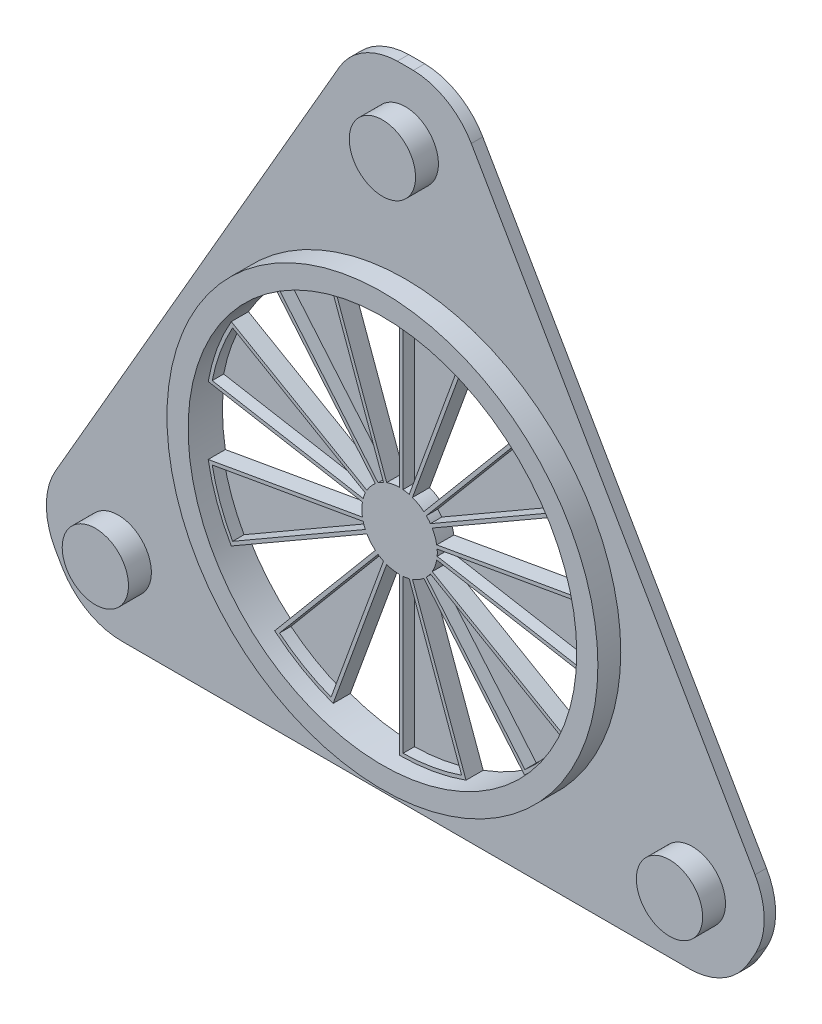
SolidWorks part; units mm, degrees
ref_plane "Спереди" through (0, 0, 0) normal (0, 0, 1) x (1, 0, 0)
ref_plane "Сверху" through (0, 0, 0) normal (0, 1, 0) x (1, 0, 0)
ref_plane "Справа" through (0, 0, 0) normal (1, 0, 0) x (0, 0, -1)
sketch "Sketch1" plane through (0, 0, 0) normal (0, 0, 1) x (1, 0, 0)
  line L0 (3.9, 6.755) -> (7.8, 0) construction
  line L2 (5.85, 10.1325) -> (11.7, 0) construction
  line L4 (7.8, 13.51) -> (15.6, 0) construction
  circle A61 centre (0, 0) radius 20
  circle A131 centre (0, 0) radius 1.25
  circle A484 centre (3.9, 0) radius 1.25
  circle A485 centre (7.8, 0) radius 1.25
  circle A486 centre (11.7, 0) radius 1.25
  circle A487 centre (15.6, 0) radius 1.25
  circle A488 centre (1.95, -3.3775) radius 1.25
  circle A489 centre (3.9, -6.755) radius 1.25
  circle A490 centre (5.85, -10.1325) radius 1.25
  circle A491 centre (7.8, -13.51) radius 1.25
  circle A492 centre (-1.95, -3.3775) radius 1.25
  circle A493 centre (-3.9, -6.755) radius 1.25
  circle A494 centre (-5.85, -10.1325) radius 1.25
  circle A495 centre (-7.8, -13.51) radius 1.25
  circle A496 centre (-3.9, 0) radius 1.25
  circle A497 centre (-7.8, 0) radius 1.25
  circle A498 centre (-11.7, 0) radius 1.25
  circle A499 centre (-15.6, 0) radius 1.25
  circle A500 centre (-1.95, 3.3775) radius 1.25
  circle A501 centre (-3.9, 6.755) radius 1.25
  circle A502 centre (-5.85, 10.1325) radius 1.25
  circle A503 centre (-7.8, 13.51) radius 1.25
  circle A504 centre (1.95, 3.3775) radius 1.25
  circle A505 centre (3.9, 6.755) radius 1.25
  circle A506 centre (5.85, 10.1325) radius 1.25
  circle A507 centre (7.8, 13.51) radius 1.25
  circle A508 centre (5.85, 3.3775) radius 1.25
  circle A509 centre (7.8, 6.755) radius 1.25
  circle A510 centre (9.75, 3.3775) radius 1.25
  circle A511 centre (11.7, 6.755) radius 1.25
  circle A512 centre (9.7491, 10.1341) radius 1.25
  circle A513 centre (13.6509, 3.3759) radius 1.25
  circle A514 centre (5.85, -3.3791) radius 1.25
  circle A515 centre (9.75, -3.3791) radius 1.25
  circle A516 centre (7.8, -6.7566) radius 1.25
  circle A517 centre (11.7, -6.7566) radius 1.25
  circle A518 centre (9.7491, -10.1356) radius 1.25
  circle A519 centre (13.6509, -3.3775) radius 1.25
  circle A520 centre (-0.0013, -6.7573) radius 1.25
  circle A521 centre (1.9487, -10.1348) radius 1.25
  circle A522 centre (-1.9513, -10.1348) radius 1.25
  circle A523 centre (-0.0013, -13.5123) radius 1.25
  circle A524 centre (-3.9032, -13.5123) radius 1.25
  circle A525 centre (3.9005, -13.5123) radius 1.25
  circle A526 centre (-5.8527, -3.3791) radius 1.25
  circle A527 centre (-7.8027, -6.7566) radius 1.25
  circle A528 centre (-9.7527, -3.3791) radius 1.25
  circle A529 centre (-11.7027, -6.7566) radius 1.25
  circle A530 centre (-13.6536, -3.3775) radius 1.25
  circle A531 centre (-9.7518, -10.1356) radius 1.25
  circle A532 centre (-5.8527, 3.3775) radius 1.25
  circle A533 centre (-9.7527, 3.3775) radius 1.25
  circle A534 centre (-7.8027, 6.755) radius 1.25
  circle A535 centre (-11.7027, 6.755) radius 1.25
  circle A536 centre (-9.7518, 10.1341) radius 1.25
  circle A537 centre (-13.6536, 3.3759) radius 1.25
  circle A538 centre (-0.0014, 6.7558) radius 1.25
  circle A539 centre (-1.9514, 10.1333) radius 1.25
  circle A540 centre (1.9486, 10.1333) radius 1.25
  circle A541 centre (-0.0014, 13.5108) radius 1.25
  circle A542 centre (3.9005, 13.5108) radius 1.25
  circle A543 centre (-3.9032, 13.5108) radius 1.25
  circle A544 centre (13.65, -1.1258) radius 2.2517 construction
  circle A545 centre (11.7009, -4.5044) radius 2.2522 construction
  circle A546 centre (9.75, -7.8834) radius 2.2522 construction
  circle A547 centre (7.7987, -11.2591) radius 2.2509 construction
  circle A548 centre (13.65, -1.1258) radius 0.65
  circle A549 centre (11.7009, -4.5044) radius 0.65
  circle A550 centre (9.75, -7.8834) radius 0.65
  circle A551 centre (7.7987, -11.2591) radius 0.65
  circle A552 centre (9.75, -1.1258) radius 0.65
  circle A553 centre (7.8009, -4.5044) radius 0.65
  circle A554 centre (5.85, -7.8834) radius 0.65
  circle A555 centre (3.8987, -11.2591) radius 0.65
  circle A556 centre (5.85, -1.1258) radius 0.65
  circle A557 centre (3.9009, -4.5044) radius 0.65
  circle A558 centre (1.95, -7.8834) radius 0.65
  circle A559 centre (-0.0013, -11.2591) radius 0.65
  circle A560 centre (1.95, -1.1258) radius 0.65
  circle A561 centre (0.0009, -4.5044) radius 0.65
  circle A562 centre (-1.95, -7.8834) radius 0.65
  circle A563 centre (-3.9013, -11.2591) radius 0.65
  circle A564 centre (-1.95, -1.1258) radius 0.65
  circle A565 centre (-3.8991, -4.5044) radius 0.65
  circle A566 centre (-5.85, -7.8834) radius 0.65
  circle A567 centre (-7.8013, -11.2591) radius 0.65
  circle A568 centre (-5.85, -1.1258) radius 0.65
  circle A569 centre (-7.7991, -4.5044) radius 0.65
  circle A570 centre (-9.75, -7.8834) radius 0.65
  circle A572 centre (-9.75, -1.1258) radius 0.65
  circle A573 centre (-11.6991, -4.5044) radius 0.65
  circle A576 centre (-13.65, -1.1258) radius 0.65
  circle A587 centre (0, 2.2517) radius 2.2517 construction
  circle A588 centre (0, 2.2517) radius 0.65
  circle A589 centre (3.9, 2.2517) radius 0.65
  circle A590 centre (7.8, 2.2517) radius 0.65
  circle A591 centre (11.7, 2.2517) radius 0.65
  circle A592 centre (15.6, 2.2517) radius 0.65
  circle A593 centre (1.9491, 5.6297) radius 2.2522 construction
  circle A594 centre (1.9491, 5.6297) radius 0.65
  circle A595 centre (5.8491, 5.6297) radius 0.65
  circle A596 centre (9.7491, 5.6297) radius 0.65
  circle A597 centre (13.6491, 5.6297) radius 0.65
  circle A598 centre (3.8991, 9.0072) radius 2.2522 construction
  circle A599 centre (3.8991, 9.0072) radius 0.65
  circle A600 centre (7.7991, 9.0072) radius 0.65
  circle A601 centre (11.6991, 9.0072) radius 0.65
  circle A602 centre (5.85, 12.3842) radius 2.2517 construction
  circle A603 centre (5.85, 12.3842) radius 0.65
  circle A604 centre (9.75, 12.3842) radius 0.65
  circle A605 centre (5.85, -14.6358) radius 0.65
  circle A606 centre (1.9509, -14.6353) radius 0.65
  circle A607 centre (-1.9491, -14.6353) radius 0.65
  circle A608 centre (-5.85, -14.6358) radius 0.65
  circle A609 centre (-15.6, 2.2517) radius 0.65
  circle A610 centre (-13.65, 5.6281) radius 0.65
  circle A611 centre (-11.7, 9.0056) radius 0.65
  circle A612 centre (-9.75, 12.3842) radius 0.65
  circle A613 centre (-5.85, 12.3842) radius 0.65
  circle A614 centre (-1.95, 12.3842) radius 0.65
  circle A615 centre (1.95, 12.3842) radius 0.65
  circle A616 centre (-7.8, 9.0056) radius 0.65
  circle A617 centre (-9.75, 5.6281) radius 0.65
  circle A618 centre (-11.7, 2.2517) radius 0.65
  circle A619 centre (-3.9, 9.0056) radius 0.65
  circle A620 centre (-5.85, 5.6281) radius 0.65
  circle A621 centre (-7.8, 2.2517) radius 0.65
  circle A622 centre (0, 9.0056) radius 0.65
  circle A623 centre (-1.95, 5.6281) radius 0.65
  circle A624 centre (-3.9, 2.2517) radius 0.65
  circle A625 centre (-15.5991, -4.5044) radius 0.65
  circle A626 centre (-13.65, -7.8834) radius 0.65
  circle A627 centre (-17.55, -7.8834) radius 0.65
  circle A628 centre (-19.5013, -11.2591) radius 0.65
  circle A629 centre (-15.6013, -11.2591) radius 0.65
  circle A630 centre (-11.7013, -11.2591) radius 0.65
  point P51 (0, 0)
  point P125 (-0.0013, -0.0008)
  point P231 (0, 0)
  dimension "D1" = 5
  dimension "D3" = 6
  dimension "D5" = 8
  dimension "D7" = 4
  dimension "D11" = 4
  dimension "D2" = 6
  dimension "D6" = 5
  dimension "D8" = 3
  dimension "D9" = 2
  dimension "D4" = 1.3
  dimension "D10" = 3
ref_plane "Plane1" through (0, 0, 10) normal (0, 0, 1) x (1, 0, 0)
sketch "Sketch2" plane through (0, 0, 10) normal (0, 0, 1) x (1, 0, 0)
  line L0 (0, 2.9883) -> (0, 17)
  line L62 (1.0221, 2.8081) -> (5.8143, 15.9748)
  line L71 (1.9208, 2.2892) -> (10.9274, 13.0228)
  line L92 (2.588, 1.4942) -> (14.7224, 8.5)
  line L101 (2.9429, 0.5189) -> (16.7417, 2.952)
  line L110 (2.9429, -0.5189) -> (16.7417, -2.952)
  line L119 (2.588, -1.4942) -> (14.7224, -8.5)
  line L124 (1.9208, -2.2892) -> (10.9274, -13.0228)
  line L133 (1.0221, -2.8081) -> (5.8143, -15.9748)
  line L142 (0, -2.9883) -> (0, -17)
  line L151 (-1.0221, -2.8081) -> (-5.8143, -15.9748)
  line L160 (-1.9208, -2.2892) -> (-10.9274, -13.0228)
  line L165 (-2.588, -1.4942) -> (-14.7224, -8.5)
  line L168 (-2.9429, -0.5189) -> (-16.7417, -2.952)
  line L171 (-2.9429, 0.5189) -> (-16.7417, 2.952)
  line L174 (-2.588, 1.4942) -> (-14.7224, 8.5)
  line L177 (-1.9208, 2.2892) -> (-10.9274, 13.0228)
  line L180 (-1.0221, 2.8081) -> (-5.8143, 15.9748)
  line L183 (0.3, 3.2863) -> (0.3, 16.6948)
  line L185 (5.4281, 15.7906) -> (0.8421, 3.1908)
  line L186 (14.3082, 8.6072) -> (2.696, 1.903)
  line L187 (2.3422, 2.3246) -> (10.9611, 12.5962)
  line L188 (16.4933, -2.6036) -> (3.2885, -0.2752)
  line L189 (3.2885, 0.2752) -> (16.4933, 2.6036)
  line L190 (10.9611, -12.5962) -> (2.3422, -2.3246)
  line L191 (2.696, -1.903) -> (14.3082, -8.6072)
  line L192 (0.3, -16.6948) -> (0.3, -3.2863)
  line L193 (0.8421, -3.1908) -> (5.4281, -15.7906)
  line L194 (-10.5014, -12.9818) -> (-1.8826, -2.7103)
  line L195 (-1.4059, -2.9855) -> (-5.9919, -15.5854)
  line L196 (-16.3891, -3.1945) -> (-3.1843, -0.8661)
  line L197 (-2.996, -1.3834) -> (-14.6082, -8.0876)
  line L198 (-14.6082, 8.0876) -> (-2.996, 1.3834)
  line L199 (-3.1843, 0.8661) -> (-16.3891, 3.1945)
  line L200 (-5.9919, 15.5854) -> (-1.4059, 2.9855)
  line L201 (-1.8826, 2.7103) -> (-10.5014, 12.9818)
  circle A52 centre (0, 0) radius 17
  circle A53 centre (0, 0) radius 18.85
  circle A199 centre (0, 0) radius 2.9883
  circle A245 centre (0, 0) radius 18.85
  circle A246 centre (0, 0) radius 3.3
  circle A247 centre (0, 0) radius 16.6975
  point P39 (0, 0)
  point P80 (0, 0)
  point P108 (0, 0)
  dimension "D1" = 18
  dimension "D4" = 9
  dimension "D2" = 0.3
  dimension "D3" = 0.3
extrude "Boss-Extrude1" add sketch "Sketch2" against normal blind 3
sketch "Sketch11" plane through (0, 0, 7) normal (0, 0, -1) x (-1, 0, 0)
  line L0 (0, 2.9883) -> (0, 18.85)
  line L1 (1.0221, 2.8081) -> (6.4471, 17.7132)
  line L2 (2.588, 1.4942) -> (16.3246, 9.425)
  line L3 (1.9208, 2.2892) -> (12.1165, 14.4399)
  line L4 (2.9429, -0.5189) -> (18.5636, -3.2733)
  line L5 (2.9429, 0.5189) -> (18.5636, 3.2733)
  line L6 (1.9208, -2.2892) -> (12.1165, -14.4399)
  line L7 (2.588, -1.4942) -> (16.3246, -9.425)
  line L8 (0, -2.9883) -> (0, -18.85)
  line L9 (1.0221, -2.8081) -> (6.4471, -17.7132)
  line L10 (-1.9208, -2.2892) -> (-12.1165, -14.4399)
  line L11 (-1.0221, -2.8081) -> (-6.4471, -17.7132)
  line L12 (-2.9429, -0.5189) -> (-18.5636, -3.2733)
  line L13 (-2.588, -1.4942) -> (-16.3246, -9.425)
  line L14 (-2.588, 1.4942) -> (-16.3246, 9.425)
  line L15 (-2.9429, 0.5189) -> (-18.5636, 3.2733)
  line L16 (-1.0221, 2.8081) -> (-6.4471, 17.7132)
  line L17 (-1.9208, 2.2892) -> (-12.1165, 14.4399)
  circle A0 centre (0, 0) radius 2.9883
  circle A1 centre (0, 0) radius 18.85
  circle A5 centre (0, 0) radius 18.85 construction
  arc A6 (0, 18.85) -> (6.4471, 17.7132) centre (0, 0) cw
  arc A8 (12.1165, 14.4399) -> (16.3246, 9.425) centre (0, 0) cw
  arc A10 (18.5636, 3.2733) -> (18.5636, -3.2733) centre (0, 0) cw
  arc A12 (16.3246, -9.425) -> (12.1165, -14.4399) centre (0, 0) cw
  arc A14 (6.4471, -17.7132) -> (0, -18.85) centre (0, 0) cw
  arc A16 (-6.4471, -17.7132) -> (-12.1165, -14.4399) centre (0, 0) cw
  arc A18 (-16.3246, -9.425) -> (-18.5636, -3.2733) centre (0, 0) cw
  arc A20 (-18.5636, 3.2733) -> (-16.3246, 9.425) centre (0, 0) cw
  arc A22 (-12.1165, 14.4399) -> (-6.4471, 17.7132) centre (0, 0) cw
  point P63 (0, 0)
  dimension "D1" = 9
extrude "Boss-Extrude7" add sketch "Sketch11" against normal blind 0.5 contours L0 A1 L16 A0 | L17 A1 L14 A0 | L15 A1 L12 A0 | L13 A1 L10 A0 | L11 A1 L8 A0 | L9 A1 L6 A0 | L7 A1 L4 A0 | L5 A1 L2 A0 | L3 A1 L1 A0
sketch "Sketch13" plane through (0, 0, 7) normal (0, 0, -1) x (-1, 0, 0)
  circle A0 centre (0, 0) radius 3.3
extrude "Boss-Extrude8" [suppressed] add sketch "Sketch13" against normal blind 3
sketch "Sketch14" plane through (0, 0, 10) normal (0, 0, 1) x (1, 0, 0)
  circle A0 centre (0, 0) radius 17
  arc A1 (0, 17) -> (-5.8143, 15.9748) centre (0, 0) ccw construction
sketch "Sketch9" plane through (0, 0, 10) normal (0, 0, 1) x (1, 0, 0)
  circle A0 centre (0, 0) radius 3.0981
sketch "Sketch16" plane through (0, 0, 9) normal (0, 0, 1) x (1, 0, 0)
  circle A0 centre (0, 0) radius 3.3
sketch "Sketch17" plane through (0, 0, 7) normal (0, 0, -1) x (-1, 0, 0)
  circle A0 centre (0, 0) radius 3.3
extrude "Boss-Extrude9" add sketch "Sketch17" against normal blind 2
extrude "Boss-Extrude5" add sketch "Sketch9" against normal up to surface (3 mm away)
sketch "Sketch3" plane through (0, 0, 7) normal (0, 0, -1) x (-1, 0, 0)
  circle A0 centre (0, 0) radius 17.6
  circle A1 centre (0, 0) radius 35
  circle M33 centre (0, 0) radius 18.85
extrude "Boss-Extrude2" add sketch "Sketch3" against normal blind 1 contours A1 M33
sketch "Sketch4" plane through (0, 0, 7) normal (0, 0, -1) x (-1, 0, 0)
  circle A0 centre (0, 0) radius 29 construction
  circle A1 centre (0, 29) radius 2.9
  circle A2 centre (25.1147, -14.5) radius 2.9
  circle A3 centre (-25.1147, -14.5) radius 2.9
  point P11 (0, 0)
  dimension "D1" = 3
extrude "Boss-Extrude3" add sketch "Sketch4" against normal blind 3
sketch "Sketch6" plane through (0, 0, 8) normal (0, 0, -1) x (-1, 0, 0)
  circle A0 centre (0, 30) radius 5
  circle A2 centre (25.9808, -15) radius 5
  circle A3 centre (-25.9808, -15) radius 5
  point P10 (0, 0)
  dimension "D1" = 3
extrude "Boss-Extrude4" add sketch "Sketch6" along normal blind 1
sketch "Sketch7" plane through (0, 0, 7) normal (0, 0, -1) x (-1, 0, 0)
  line L1 (0, 42) -> (-36.3731, -21)
  line L2 (-36.3731, -21) -> (36.3731, -21)
  line L3 (36.3731, -21) -> (0, 42)
  circle A2 centre (0, 0) radius 21 construction
  circle A3 centre (0, 0) radius 59.1314
extrude "Cut-Extrude1" cut sketch "Sketch7" against normal blind 10
fillet "Fillet1" radius 6 6 edges at (-32.1865, -13.7487, 7.5) (-4.1865, 34.7487, 7.5) (28, -21, 7.5) (-28, -21, 7.5) (4.1865, 34.7487, 7.5) (32.1865, -13.7487, 7.5)
sketch "Sketch18" plane through (0, 0, 8) normal (0, 0, 1) x (1, 0, 0)
  circle A0 centre (0, 0) radius 17
sketch "Sketch19" plane through (0, 0, 10) normal (0, 0, 1) x (1, 0, 0)
  circle A0 centre (0, 0) radius 17
extrude "Cut-Extrude3" cut sketch "Sketch19" against normal blind 1.5
